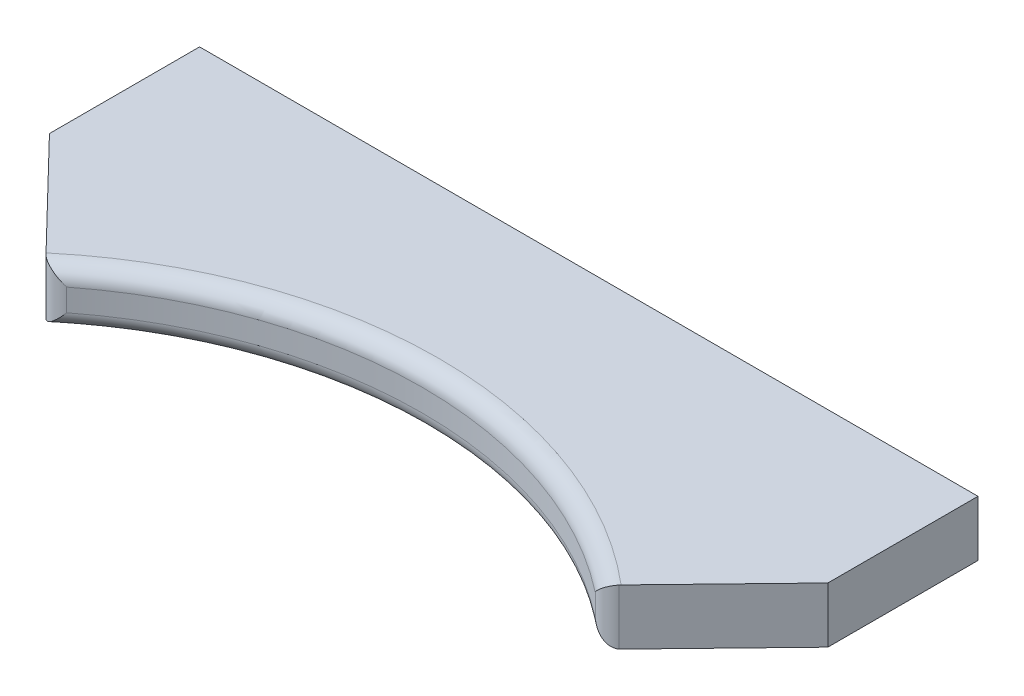
SolidWorks part; units mm, degrees
ref_plane "Front Plane" through (0, 0, 0) normal (0, 0, 1) x (1, 0, 0)
ref_plane "Top Plane" through (0, 0, 0) normal (0, 1, 0) x (1, 0, 0)
ref_plane "Right Plane" through (0, 0, 0) normal (1, 0, 0) x (0, 0, -1)
sketch "Sketch1" plane through (0, 0, 0) normal (0, 1, 0) x (1, 0, 0)
  line L3 (-44.45, 68.072) -> (44.45, 68.072)
  line L4 (44.45, 68.072) -> (44.45, 50.927)
  line L5 (44.45, 50.927) -> (31.5107, 37.553)
  line L6 (-44.45, 68.072) -> (-44.45, 50.927)
  line L7 (-44.45, 50.927) -> (-31.5107, 37.553)
  arc A0 (31.5107, 37.553) -> (-31.5107, 37.553) centre (0, 0) ccw
  dimension "D1" = 98.044
  dimension "D7" = 17.145
  dimension "D8" = 17.145
extrude "Boss-Extrude1" add sketch "Sketch1" along normal blind 6.35
fillet "Fillet1" radius 1.905 4 edges at (31.5107, 3.175, -37.553) (-31.5107, 3.175, -37.553) (0, 0, -49.022) (0, 6.35, -49.022)
